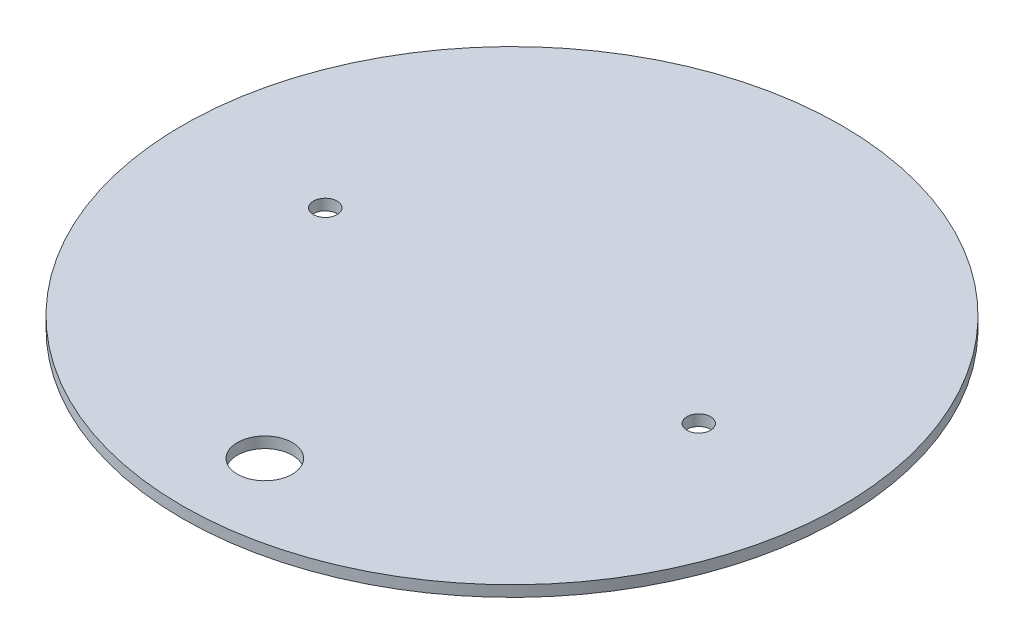
SolidWorks part; units mm, degrees
ref_plane "Front Plane" through (0, 0, 0) normal (0, 0, 1) x (1, 0, 0)
ref_plane "Top Plane" through (0, 0, 0) normal (0, 1, 0) x (1, 0, 0)
ref_plane "Right Plane" through (0, 0, 0) normal (1, 0, 0) x (0, 0, -1)
sketch "Sketch1" plane through (0, 0, 0) normal (0, 1, 0) x (1, 0, 0)
  line L0 (-60, 0) -> (60, 0) construction
  line L1 (0, 60) -> (0, -60) construction
  circle A0 centre (0, 0) radius 60
  circle A1 centre (-34, 0) radius 2.15
  circle A2 centre (34, 0) radius 2.15
  circle A3 centre (0, -45) radius 5
  dimension "D1" = 120
  dimension "D4" = 4.3
  dimension "D5" = 4.3
  dimension "D6" = 10
  dimension "D2" = 68
  dimension "D3" = 34
  dimension "D7" = 45
  dimension "D8" = 94
  dimension "D9" = 26
  dimension "D10" = 60
  dimension "D11" = 60
  dimension "D12" = 105
extrude "Boss-Extrude1" add sketch "Sketch1" along normal blind 2
